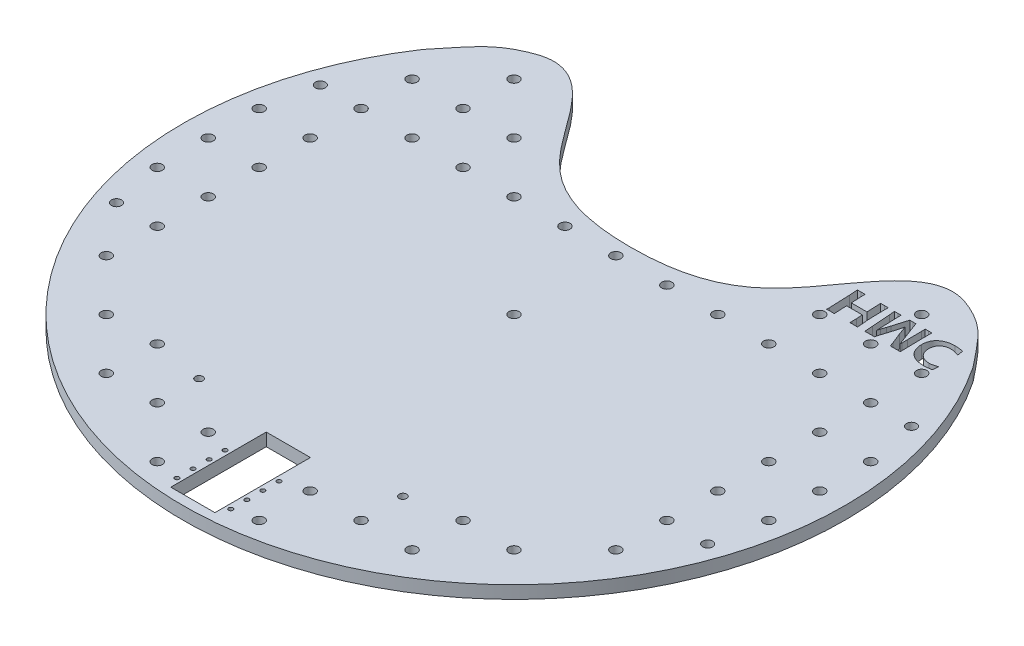
SolidWorks part; units mm, degrees
material "Oak"
ref_plane "Front Plane" through (0, 0, 0) normal (0, 0, 1) x (1, 0, 0)
ref_plane "Top Plane" through (0, 0, 0) normal (0, 1, 0) x (1, 0, 0)
ref_plane "Right Plane" through (0, 0, 0) normal (1, 0, 0) x (0, 0, -1)
sketch "Sketch1" plane through (0, 0, 0) normal (0, 1, 0) x (1, 0, 0)
  circle A0 centre (0, 0) radius 164.975
  dimension "D1" = 329.95
extrude "Boss-Extrude1" add sketch "Sketch1" along normal blind 6.35
ref_point "Point1"
sketch "Sketch2" plane through (0, 0, 0) normal (0, -1, 0) x (1, 0, 0)
  line L0 (0, -1000) -> (0, 49000) construction
  line L1 (-1000, 0) -> (49000, 0) construction
  circle A0 centre (147.32, -50.8) radius 4.7625 construction
  circle A1 centre (147.32, 50.8) radius 4.7625 construction
  circle A2 centre (-147.32, -50.8) radius 4.7625 construction
  circle A3 centre (-147.32, 50.8) radius 4.7625 construction
  point P0 (147.32, -50.8)
  dimension "D1" = 147.32
  dimension "D2" = 50.8
hole_wizard "#10 Clearance Hole1" positions "Sketch4" profile "Sketch3" hole size "#10" standard "Ansi Inch" end condition through all
sketch "Sketch4" plane through (0, 6.35, 0) normal (0, 1, 0) x (-1, 0, 0)
  point P1 (147.32, 50.8)
  point P4 (147.32, -50.8)
  point P7 (-147.32, -50.8)
  point P10 (-147.32, 50.8)
sketch "Sketch3" plane through (-147.32, 6.35, 50.8) normal (1, 0, 0) x (0, 0, 1)
  line L0 (0, 0) -> (0, 6.35)
  line L1 (0, 6.35) -> (2.4892, 6.35)
  line L2 (2.4892, 6.35) -> (2.4892, 0)
  line L5 (2.4892, 0) -> (0, 0)
  line L11 (0, -6.35) -> (0, 107.95) construction
  dimension "Thru Hole Dia." = 4.9784
  dimension "Thru Hole Depth" = 6.35
sketch "Sketch5" plane through (0, 6.35, 0) normal (0, 1, 0) x (1, 0, 0)
  line L0 (0, 201000) -> (0, -249000) construction
  line L1 (-50.8, -55.3589) -> (50.8, -55.3589) construction
  line L2 (-50.8, -55.3589) -> (-50.8, -156.9589) construction
  line L3 (-50.8, -156.9589) -> (50.8, -156.9589) construction
  line L4 (50.8, -55.3589) -> (50.8, -156.9589) construction
  line L5 (-50.8, -55.3589) -> (50.8, -156.9589) construction
  line L6 (-50.8, -156.9589) -> (50.8, -55.3589) construction
  line L7 (0, -106.1589) -> (0, 58.1068) construction
  circle A0 centre (0, 0) radius 164.975 construction
  circle A2 centre (147.32, 50.8) radius 2.4892 construction
  spline S0 degree 3 poles (-137.1735, 91.6525) (-125.7052, 105.9966) (-120.8705, 112.2721) (-90.3531, 124.7653) (-63.3632, 88.0034) (-42.1548, 58.1068) (0, 58.1068) knots 0 0 0 0 0.216331 0.275014 0.586828 1 1 1 1
  spline S1 degree 3 poles (137.1735, 91.6525) (125.7052, 105.9966) (120.8705, 112.2721) (90.3531, 124.7653) (63.3632, 88.0034) (42.1548, 58.1068) (0, 58.1068) knots 0 0 0 0 0.216331 0.275014 0.586828 1 1 1 1
  point P0 (0, -106.1589)
  dimension "D1" = 101.6
  dimension "D2" = 101.6
extrude "Cut-Extrude1" cut sketch "Sketch5" against normal through all and the other way through all contours S0 S1
hole_wizard "#10 Clearance Hole2" positions "Sketch9" profile "Sketch8" hole size "#10" standard "Ansi Inch"
sketch "Sketch9" plane through (0, 0, 0) normal (0, -1, 0) x (1, 0, 0)
  point P1 (0, 0)
sketch "Sketch8" plane through (0, 0, 0) normal (1, 0, 0) x (0, 0, -1)
  line L0 (0, 0) -> (0, 7.8838)
  line L1 (0, 7.8838) -> (2.5527, 6.35)
  line L2 (2.5527, 6.35) -> (2.5527, 0)
  line L5 (2.5527, 0) -> (0, 0)
  line L10 (0, 7.8838) -> (-2.5527, 6.35) construction
  line L11 (0, -6.35) -> (0, 107.95) construction
  dimension "Hole Dia." = 5.1054
  dimension "Hole Depth" = 6.35
  dimension "Drill Angle" = 118
ref_plane "Plane1" through (0, 0, 0) normal (1, 0, 0) x (0, 0, -1)
pattern_linear "LPattern2" count 7 spacing 25.4 along (-1, 0, 0) count 7 spacing 25.4 along (0, 0, 1) skipping (0, 1), (0, 2), (0, 3), (0, 4), (0, 5), (0, 6), (1, 0), (1, 1), (1, 2), (1, 3), (1, 4), (2, 0), (2, 1), (2, 2), (2, 3), (2, 4), (2, 6), (3, 0), (3, 1), (3, 2), (3, 3), (3, 6), (4, 0), (4, 1), (4, 2), (4, 3), (4, 5), (4, 6), (5, 4), (5, 5), (5, 6), (6, 2), (6, 3), (6, 4), (6, 5), (6, 6) of "#10 Clearance Hole2"
pattern_linear "LPattern3" count 5 spacing 25.4 along (0, 0, -1) count 7 spacing 25.4 along (-1, 0, 0) skipping (0, 1), (0, 2), (0, 3), (0, 4), (1, 0), (1, 1), (1, 2), (1, 3), (1, 4), (2, 6), (3, 0), (3, 1), (3, 2), (3, 6), (4, 0), (4, 1), (4, 2), (4, 3), (4, 5), (4, 6) of "#10 Clearance Hole2"
sketch "Sketch10" plane through (0, 0, 0) normal (0, -1, 0) x (1, 0, 0)
  line L0 (0, -58.1068) -> (73.66, -58.1068) construction
  line L1 (73.66, -58.1068) -> (73.66, -96.2068) construction
  line L2 (73.66, -96.2068) -> (124.46, -96.2068) construction
  text T0 "HMC" font "Eras Demi ITC" height 16.002
  dimension "D1" = 73.66
  dimension "D2" = 38.1
  dimension "D3" = 50.8
extrude "Cut-Extrude2" cut sketch "Sketch10" against normal through all
mirror "Mirror1" about plane through (0, 0, 0) normal (1, 0, 0) of "LPattern3", "LPattern2"
sketch "Sketch12" plane through (0, 6.35, 0) normal (0, 1, 0) x (1, 0, 0)
  line L0 (0, -112.468) -> (0, -160.068) construction
  line L1 (-11, -112.468) -> (-11, -160.068)
  line L2 (-11, -112.468) -> (11, -112.468)
  line L3 (-11, -160.068) -> (11, -160.068)
  line L4 (11, -112.468) -> (11, -160.068)
  line L5 (-11, -112.468) -> (11, -160.068) construction
  line L6 (-11, -160.068) -> (11, -112.468) construction
  line L9 (0, 201000) -> (0, -249000) construction
  arc A0 (-137.1735, 91.6525) -> (137.1735, 91.6525) centre (0, 0) ccw construction
  point P4 (-13.4, -130.568)
  point P5 (0, -136.268)
  point P6 (-13.4, -138.568)
  point P7 (-13.4, -146.568)
  point P12 (-13.4, -154.568)
  point P13 (0, -164.975)
  point P14 (13.4, -154.568)
  point P18 (13.4, -146.568)
  point P19 (13.4, -138.568)
  point P20 (13.4, -130.568)
  dimension "D1" = 2.4
  dimension "D2" = 8
  dimension "D3" = 18.1
  dimension "D4" = 8
  dimension "D5" = 8
  dimension "D6" = 22
  dimension "D7" = 47.6
  dimension "D8" = 28.707
extrude "Cut-Extrude3" cut sketch "Sketch12" against normal through all
hole_wizard "#4 Clearance Hole1" positions "Sketch22" profile "Sketch21" hole size "#4" standard "Ansi Inch" end condition through all
sketch "Sketch22" plane through (0, 6.35, 0) normal (0, 1, 0) x (-1, 0, 0)
  point P4 (-13.4, 130.568)
  point P7 (-13.4, 138.568)
  point P10 (-13.4, 146.568)
  point P13 (-13.4, 154.568)
  point P16 (13.4, 154.568)
  point P19 (13.4, 146.568)
  point P22 (13.4, 138.568)
  point P25 (13.4, 130.568)
sketch "Sketch21" plane through (13.4, 6.35, 130.568) normal (1, 0, 0) x (0, 0, 1)
  line L0 (0, 0) -> (0, 6.35)
  line L1 (0, 6.35) -> (1.0795, 6.35)
  line L2 (1.0795, 6.35) -> (1.0795, 0)
  line L5 (1.0795, 0) -> (0, 0)
  line L11 (0, -6.35) -> (0, 107.95) construction
  dimension "Thru Hole Dia." = 2.159
  dimension "Thru Hole Depth" = 6.35
sketch "Sketch23" plane through (0, 0, 0) normal (0, -1, 0) x (1, 0, 0)
  line L0 (50.8, 156.9589) -> (-50.8, 156.9589) construction
  line L1 (50.8, 156.9589) -> (50.8, 55.3589) construction
  line L2 (50.8, 55.3589) -> (-50.8, 55.3589) construction
  line L3 (-50.8, 156.9589) -> (-50.8, 55.3589) construction
  line L4 (50.8, 156.9589) -> (-50.8, 55.3589) construction
  line L5 (50.8, 55.3589) -> (-50.8, 156.9589) construction
  line L6 (0, -181.4725) -> (0, 181.4725) construction
  arc A0 (137.1735, -91.6525) -> (-137.1735, -91.6525) centre (0, 0) ccw construction
  point P0 (0, 106.1589)
  point P5 (-50.8, 106.1589)
  point P6 (50.8, 106.1589)
  dimension "D1" = 101.6
  dimension "D2" = 101.6
hole_wizard "#6 Clearance Hole1" positions "Sketch25" profile "Sketch24" hole size "#6" standard "Ansi Inch"
sketch "Sketch25" plane through (0, 6.35, 0) normal (0, 1, 0) x (-1, 0, 0)
  point P1 (50.8, 106.1589)
  point P4 (-50.8, 106.1589)
sketch "Sketch24" plane through (-50.8, 6.35, 106.1589) normal (1, 0, 0) x (0, 0, 1)
  line L0 (0, 0) -> (0, 6.35)
  line L1 (0, 6.35) -> (1.8986, 6.35)
  line L2 (1.8986, 6.35) -> (1.8986, 0)
  line L5 (1.8986, 0) -> (0, 0)
  line L11 (0, -6.35) -> (0, 107.95) construction
  dimension "Thru Hole Dia." = 3.7973
  dimension "Thru Hole Depth" = 6.35
